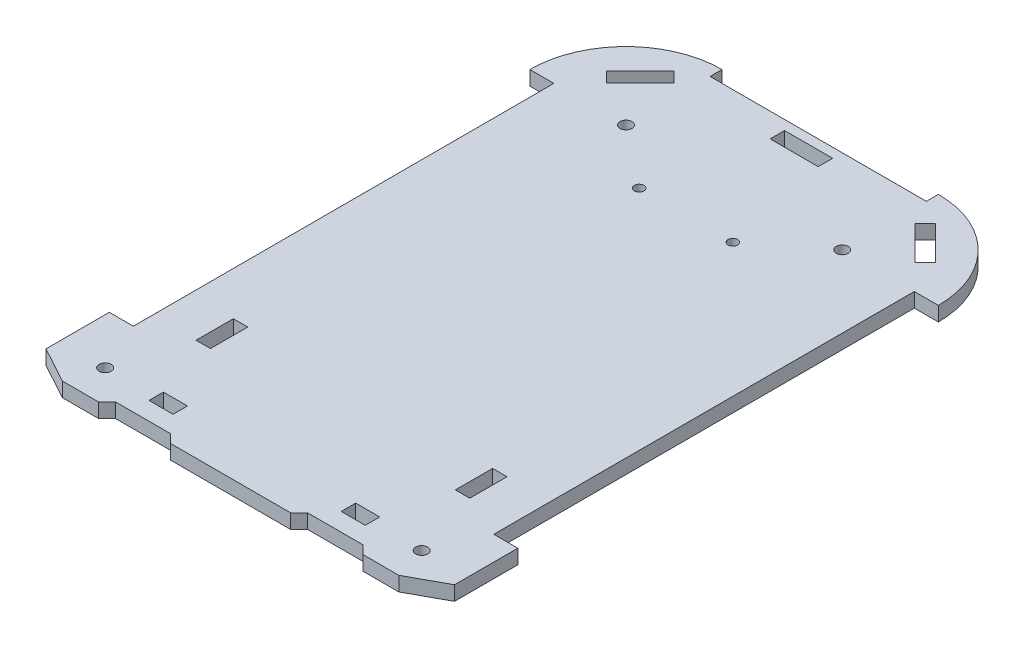
SolidWorks part; units mm, degrees
ref_plane "Front Plane" through (0, 0, 0) normal (0, 0, 1) x (1, 0, 0)
ref_plane "Top Plane" through (0, 0, 0) normal (0, 1, 0) x (1, 0, 0)
ref_plane "Right Plane" through (0, 0, 0) normal (1, 0, 0) x (0, 0, -1)
sketch "Sketch1" plane through (0, 0, 0) normal (0, 1, 0) x (1, 0, 0)
  line L0 (-45, 125.0784) -> (-45, 120.0784)
  line L2 (-85, -116.2613) -> (-85, -89.9216)
  line L4 (85, -116.2613) -> (85, -89.9216)
  line L5 (-79.9711, -124.9048) -> (80.0823, 125.0784) construction
  line L6 (-79.9175, 124.7927) -> (80, -124.9216) construction
  line L7 (-45, 120.0784) -> (45, 120.0784)
  line L8 (45, 120.0784) -> (45, 125.0784)
  line L9 (-85, 85.0784) -> (-75, 85.0784)
  line L10 (-75, 85.0784) -> (-75, -89.9216)
  line L11 (-75, -89.9216) -> (-85, -89.9216)
  line L12 (85, 85.0784) -> (75, 85.0784)
  line L13 (75, 85.0784) -> (75, -89.9216)
  line L14 (75, -89.9216) -> (85, -89.9216)
  line L15 (-85, -116.2613) -> (-69.9815, -124.4502)
  line L16 (70.0101, -124.4714) -> (85, -116.2613)
  line L43 (50.5716, 109.8107) -> (54.8142, 114.0533)
  line L44 (50.5716, 109.8107) -> (64.7137, 95.6685)
  line L45 (54.8142, 114.0533) -> (68.9564, 99.9112)
  line L46 (64.7137, 95.6685) -> (68.9564, 99.9112)
  line L47 (10, 110.0784) -> (10, 116.0784)
  line L48 (-50.1104, 110.2719) -> (-64.2525, 96.1297)
  line L49 (-50.1104, 110.2719) -> (-54.353, 114.5145)
  line L50 (-54.353, 114.5145) -> (-68.4952, 100.3724)
  line L51 (-64.2525, 96.1297) -> (-68.4952, 100.3724)
  line L52 (-69.9815, -124.4502) -> (-54.9815, -124.4502)
  line L54 (-54.9815, -124.4502) -> (-51.4459, -120.9147)
  line L55 (-51.4459, -120.9147) -> (-28.5212, -120.9147)
  line L57 (-24.9857, -124.4502) -> (25.0143, -124.4502)
  line L62 (-19.5, 65.0784) -> (19.5, 65.0784) construction
  line L63 (-10, 116.0784) -> (-10, 110.0784)
  line L64 (-10, 110.0784) -> (10, 110.0784)
  line L65 (-10, 116.0784) -> (10, 116.0784)
  line L86 (-28.5212, -120.9147) -> (-24.9857, -124.4502)
  line L89 (0.0143, -124.4502) -> (0.0143, -110.0155) construction
  line L90 (28.5499, -120.9147) -> (25.0143, -124.4502)
  line L91 (51.4746, -120.9147) -> (28.5499, -120.9147)
  line L92 (55.0101, -124.4502) -> (51.4746, -120.9147)
  line L93 (70.0101, -124.4714) -> (55.0101, -124.4502)
  line L94 (55.0101, -124.4502) -> (-54.9815, -124.4502) construction
  line L95 (75, -89.9216) -> (75, -81.9216) construction
  line L96 (-39.9836, -120.9147) -> (-39.9836, -110.9147) construction
  line L97 (40.0122, -120.9147) -> (40.0122, -110.9147) construction
  line L98 (-34.9836, -107.4147) -> (-34.9836, -113.4147)
  line L99 (-44.9836, -113.4147) -> (-34.9836, -113.4147)
  line L100 (-44.9836, -107.4147) -> (-34.9836, -107.4147)
  line L101 (-44.9836, -107.4147) -> (-44.9836, -113.4147)
  line L102 (45.0122, -107.4147) -> (35.0122, -107.4147)
  line L103 (35.0122, -107.4147) -> (35.0122, -113.4147)
  line L104 (45.0122, -113.4147) -> (35.0122, -113.4147)
  line L105 (45.0122, -107.4147) -> (45.0122, -113.4147)
  line L106 (75, -81.9216) -> (57, -81.9216) construction
  line L107 (0.0556, 0.0868) -> (0.0556, -82.551) construction
  line L108 (57, -81.9216) -> (57, -66.4216)
  line L109 (57, -66.4216) -> (51, -66.4216)
  line L110 (51, -66.4216) -> (51, -81.9216)
  line L111 (51, -81.9216) -> (57, -81.9216)
  line L112 (-50.8889, -66.4216) -> (-50.8889, -81.9216)
  line L113 (-56.8889, -66.4216) -> (-50.8889, -66.4216)
  line L114 (-56.8889, -81.9216) -> (-56.8889, -66.4216)
  line L115 (-50.8889, -81.9216) -> (-56.8889, -81.9216)
  arc A0 (-85, 85.0784) -> (-45, 125.0784) centre (-45, 85.0784) cw
  arc A1 (45, 125.0784) -> (85, 85.0784) centre (45, 85.0784) cw
  circle A9 centre (-45, 85.0784) radius 2.5
  circle A10 centre (45, 85.0784) radius 2.5
  circle A17 centre (-65.8579, -110.7794) radius 2.5
  circle A18 centre (65.8579, -110.7794) radius 2.5
  circle A19 centre (19.5, 65.0784) radius 2
  circle A20 centre (-19.5, 65.0784) radius 2
  point P0 (0, 0)
  point P41 (-39.9836, -110.9147)
  point P71 (0, 112.5784)
  point P76 (0, 65.0784)
  dimension "D3" = 40
  dimension "D4" = 40
  dimension "D10" = 10
  dimension "D11" = 5
  dimension "D15" = 79.9958
  dimension "D16" = 6
  dimension "D17" = 39
  dimension "D18" = 5
  dimension "D21" = 90
  dimension "D22" = 15
  dimension "D19" = 55
  dimension "D20" = 170
  dimension "D14" = 10
  dimension "D27" = 5
  dimension "D28" = 4
  dimension "D29" = 4
  dimension "D1" = 160
  dimension "D2" = 250
  dimension "D5" = 5
  dimension "D6" = 10
  dimension "D7" = 10
  dimension "D8" = 175
  dimension "D9" = 175
  dimension "D23" = 50
  dimension "D24" = 15
  dimension "D25" = 6
  dimension "D26" = 46.0977
  dimension "D30" = 6
  dimension "D31" = 6
  dimension "D32" = 20
  dimension "D33" = 20
  dimension "D34" = 6
  dimension "D35" = 8
  dimension "D36" = 18
  dimension "D37" = 15.5
  dimension "D38" = 6
extrude "Boss-Extrude1" add sketch "Sketch1" along normal blind 6
